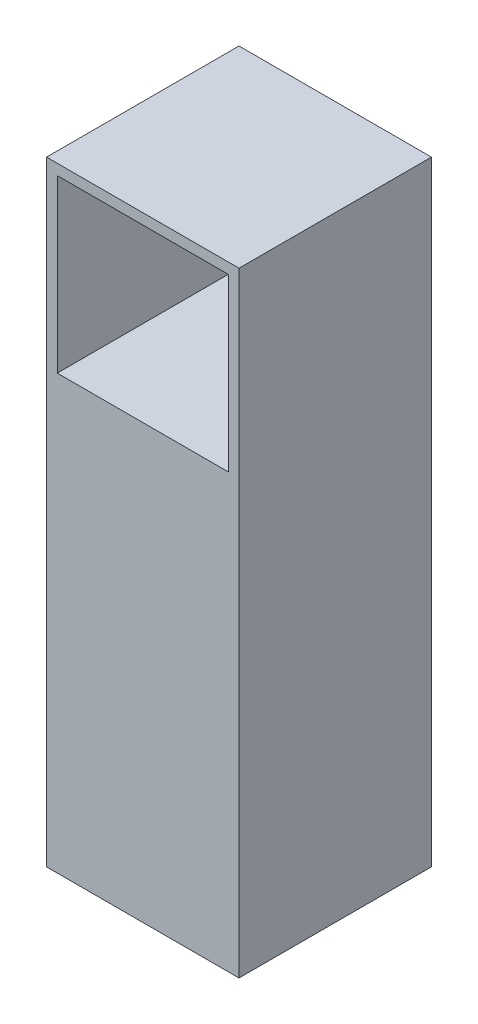
SolidWorks part; units mm, degrees
ref_plane "Front Plane" through (0, 0, 0) normal (0, 0, 1) x (1, 0, 0)
ref_plane "Top Plane" through (0, 0, 0) normal (0, 1, 0) x (1, 0, 0)
ref_plane "Right Plane" through (0, 0, 0) normal (1, 0, 0) x (0, 0, -1)
sketch "Sketch1" plane through (0, 0, 0) normal (0, 1, 0) x (1, 0, 0)
  line L1 (18, 18) -> (-18, 18)
  line L2 (18, 18) -> (18, -18)
  line L3 (18, -18) -> (-18, -18)
  line L4 (-18, 18) -> (-18, -18)
  line L5 (0, -18) -> (0, 18) construction
  line L6 (18, 0) -> (-18, 0) construction
  point P0 (0, 0)
  dimension "D1" = 36
  dimension "D2" = 36
extrude "Boss-Extrude1" add sketch "Sketch1" along normal blind 115
sketch "Sketch2" plane through (0, 0, 18) normal (0, 0, 1) x (1, 0, 0)
  line L0 (0, 113) -> (0, 115) construction
  line L1 (-16, 113) -> (16, 113)
  line L2 (-16, 113) -> (-16, 81)
  line L3 (-16, 81) -> (16, 81)
  line L4 (16, 113) -> (16, 81)
  line L5 (0, 81) -> (0, 113) construction
  line L6 (-16, 97) -> (16, 97) construction
  line L7 (-18, 115) -> (18, 115) construction
  line L8 (-16, 97) -> (-18, 97) construction
  line L9 (-18, 115) -> (-18, 0) construction
  point P148 (0, 97)
  dimension "D1" = 2
extrude "Cut-Extrude1" cut sketch "Sketch2" against normal blind 115
